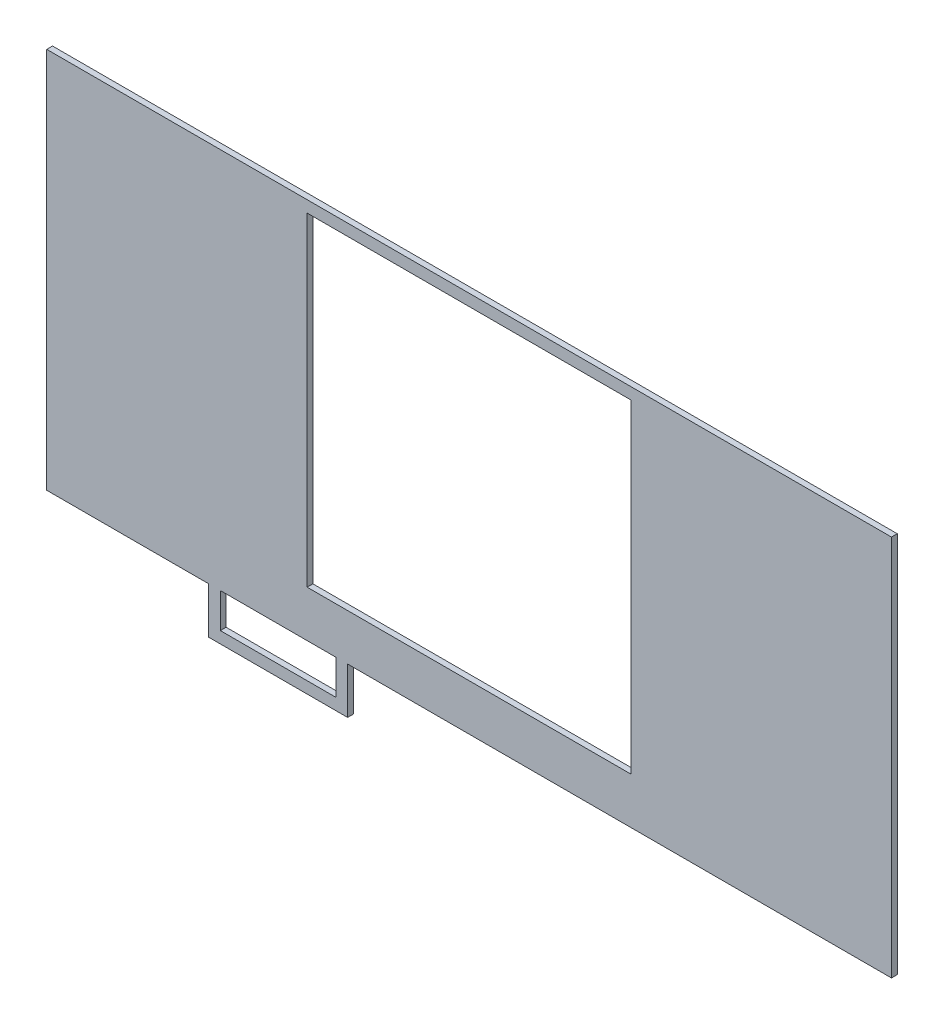
SolidWorks part; units mm, degrees
ref_plane "Alzado" through (0, 0, 0) normal (0, 0, 1) x (1, 0, 0)
ref_plane "Planta" through (0, 0, 0) normal (0, 1, 0) x (1, 0, 0)
ref_plane "Vista lateral" through (0, 0, 0) normal (1, 0, 0) x (0, 0, -1)
sketch "Croquis2" plane through (0, 0, 0) normal (0, 0, 1) x (1, 0, 0)
  line L1 (-365, -165) -> (365, -165)
  line L2 (-365, -165) -> (-365, 165)
  line L3 (-365, 165) -> (365, 165)
  line L4 (365, -165) -> (365, 165)
  line L5 (-365, -165) -> (365, 165) construction
  line L6 (-365, 165) -> (365, -165) construction
  point P0 (0, 0)
  dimension "D1" = 730
  dimension "D2" = 330
extrude "Saliente-Extruir2" add sketch "Croquis2" along normal blind 5
sketch "Croquis4" plane through (0, 0, 5) normal (0, 0, 1) x (1, 0, 0)
  line L0 (365, 165) -> (-365, 165) construction
  line L1 (140, 155) -> (-140, 155)
  line L2 (140, 155) -> (140, -125)
  line L3 (140, -125) -> (-140, -125)
  line L4 (-140, 155) -> (-140, -125)
  line L5 (365, -165) -> (365, 165) construction
  line L6 (-365, 165) -> (-365, -165) construction
  line L7 (-365, -165) -> (365, -165) construction
  dimension "D1" = 10
  dimension "D2" = 225
  dimension "D3" = 225
  dimension "D4" = 40
  dimension "D5" = 280
  dimension "D6" = 280
extrude "Cortar-Extruir1" cut sketch "Croquis4" against normal up to surface (5 mm away) up to face at (0, 0, 0)
sketch "Croquis5" plane through (0, 0, 5) normal (0, 0, 1) x (1, 0, 0)
  line L0 (-365, -165) -> (365, -165) construction
  line L1 (-225, -165) -> (-105, -165)
  line L2 (-225, -165) -> (-225, -205)
  line L3 (-225, -205) -> (-105, -205)
  line L4 (-105, -165) -> (-105, -205)
  line L5 (-365, 165) -> (-365, -165) construction
  line L7 (-215, -165) -> (-115, -165)
  line L8 (-215, -165) -> (-215, -195)
  line L9 (-215, -195) -> (-115, -195)
  line L10 (-115, -165) -> (-115, -195)
  line M8 (-365, -165) -> (365, -165)
  dimension "D1" = 140
  dimension "D2" = 10
  dimension "D3" = 10
extrude "Saliente-Extruir3" add sketch "Croquis5" against normal up to surface (5 mm away) contours L10 L9 L8 L2 L3 L4 M8 up to face at (0, 15, 0)
